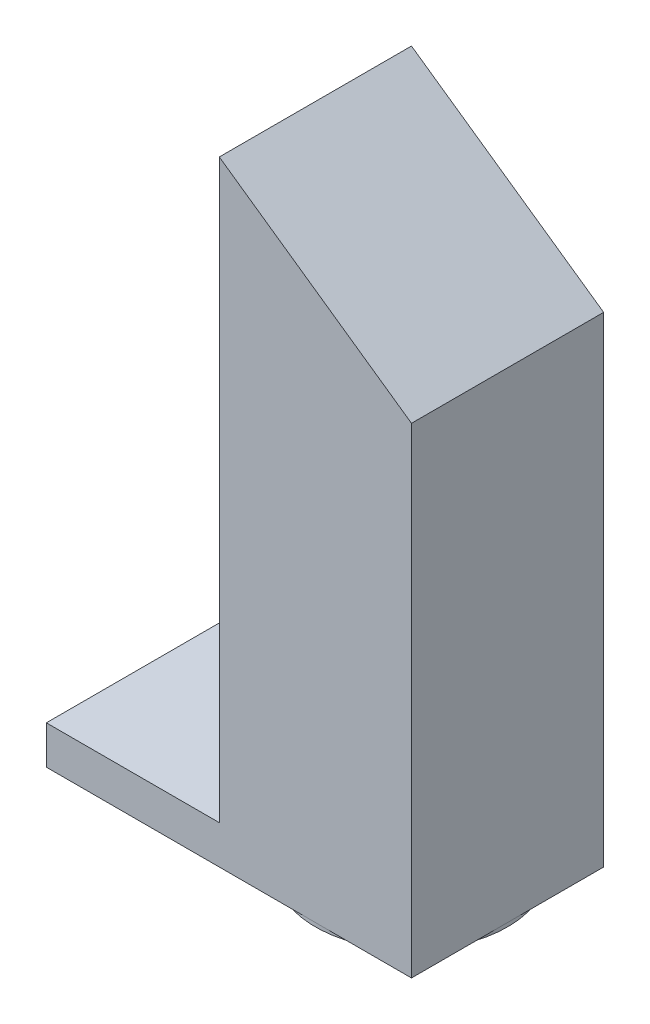
SolidWorks part; units mm, degrees
ref_plane "Front Plane" through (0, 0, 0) normal (0, 0, 1) x (1, 0, 0)
ref_plane "Top Plane" through (0, 0, 0) normal (0, 1, 0) x (1, 0, 0)
ref_plane "Right Plane" through (0, 0, 0) normal (1, 0, 0) x (0, 0, -1)
sketch "Sketch1" plane through (0, 0, 0) normal (0, 0, 1) x (1, 0, 0)
  line L0 (0, 0) -> (0, 5)
  line L5 (0, 5) -> (5, 1.499)
  line L9 (0, 0) -> (0, -10)
  line L10 (0, -10) -> (5, -10)
  line L11 (5, 1.499) -> (5, -10)
  dimension "D1" = 5
  dimension "D2" = 55
  dimension "D3" = 10
  dimension "D4" = 5
extrude "Boss-Extrude1" add sketch "Sketch1" along normal blind 5
sketch "Sketch2" plane through (0, -10, 0) normal (0, -1, 0) x (1, 0, 0)
  line L0 (0, 5) -> (0, 0) construction
  line L5 (5, 5) -> (-4.5, 5)
  line L11 (5, 5) -> (5, 0)
  line L12 (5, 0) -> (-4.5, 0)
  line L13 (-4.5, 5) -> (-4.5, 0)
  dimension "D1" = 4.5
extrude "Boss-Extrude2" add sketch "Sketch2" along normal blind 1
sketch "Sketch3" plane through (0, -11, 0) normal (0, -1, 0) x (1, 0, 0)
  line L0 (5, 5) -> (-4.5, 5) construction
  line L1 (5, 0) -> (5, 5) construction
  circle A0 centre (2.5, 2.5) radius 2.5
  dimension "D1" = 5
  dimension "D2" = 2.5
  dimension "D3" = 2.5
extrude "Boss-Extrude3" add sketch "Sketch3" along normal blind 0.1
